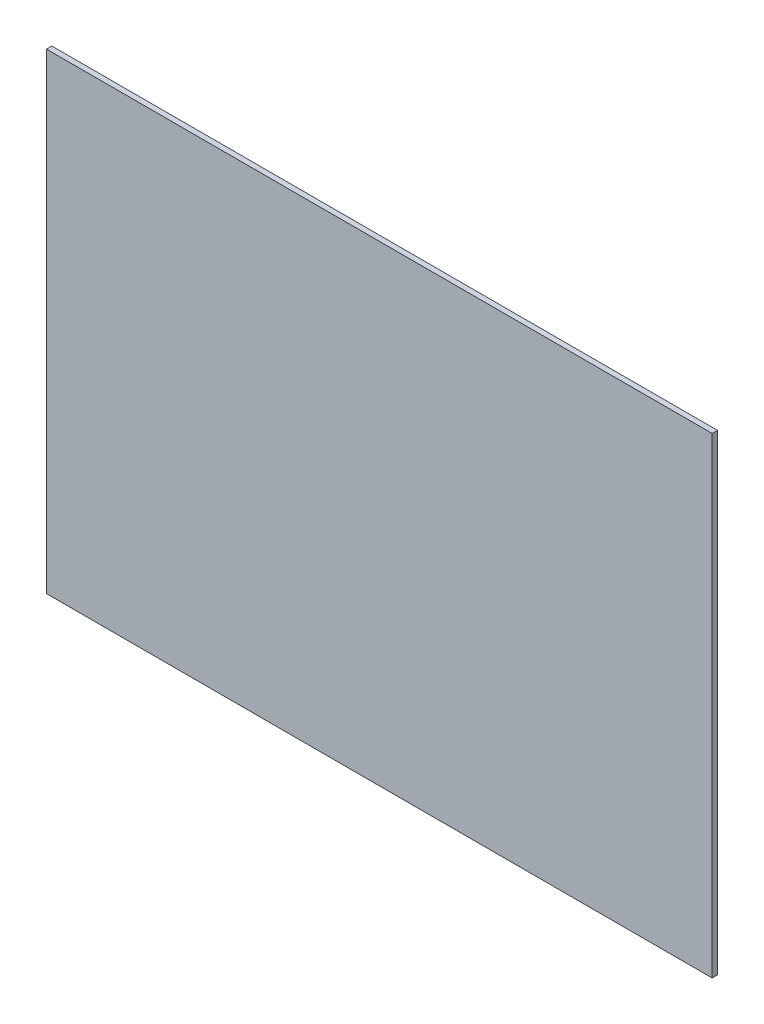
SolidWorks part; units mm, degrees
ref_plane "Front Plane" through (0, 0, 0) normal (0, 0, 1) x (1, 0, 0)
ref_plane "Top Plane" through (0, 0, 0) normal (0, 1, 0) x (1, 0, 0)
ref_plane "Right Plane" through (0, 0, 0) normal (1, 0, 0) x (0, 0, -1)
sketch "Sketch1" plane through (0, 0, 0) normal (0, 0, 1) x (1, 0, 0)
  line L1 (-196.85, -139.446) -> (196.85, -139.446)
  line L2 (-196.85, -139.446) -> (-196.85, 139.446)
  line L3 (-196.85, 139.446) -> (196.85, 139.446)
  line L4 (196.85, -139.446) -> (196.85, 139.446)
  line L5 (0, 139.446) -> (0, -139.446) construction
  line L6 (-196.85, 0) -> (196.85, 0) construction
  point P0 (0, 0)
  point P4 (-137.795, 0)
  point P5 (137.795, 0)
  point P6 (0, 97.6122)
  point P7 (0, -97.6122)
  dimension "Length" = 393.7
  dimension "Width" = 278.892
  dimension "Break" = 59.055
  dimension "D2" = 59.055
  dimension "D1" = 41.8338
  dimension "D3" = 41.8338
sketch "Sketch2" plane through (0, 0, 0) normal (1, 0, 0) x (0, 0, -1)
  line L0 (-1.5875, -139.446) -> (1.5875, -139.446)
  dimension "Thickness" = 3.175
sketch "Sketch3" plane through (0, 0, 0) normal (0, 0, 1) x (1, 0, 0)
  line L0 (-196.85, -139.446) -> (-196.85, 139.446) construction
  line L1 (-196.85, -139.446) -> (196.85, -139.446) construction
  line L2 (196.85, -139.446) -> (196.85, 139.446) construction
  line L3 (-196.85, 139.446) -> (196.85, 139.446) construction
  line L4 (-196.85, -139.446) -> (-196.85, 139.446)
  line L5 (-196.85, -139.446) -> (196.85, -139.446)
  line L6 (196.85, -139.446) -> (196.85, 139.446)
  line L7 (-196.85, 139.446) -> (196.85, 139.446)
extrude "Boss-Extrude1" add sketch "Sketch3" along normal mid plane 3.175
equation "\"D1@Boss-Extrude1\"=\"thickness@sketch2\""
equation "\"Break@Sketch1\" = \"Length@Sketch1\" * 0.15"
equation "\"D2@Sketch1\" = \"Break@Sketch1\""
equation "\"D1@Sketch1\"=\"Width@Sketch1\"*0.15"
equation "\"D3@Sketch1\"=\"D1@Sketch1\""
